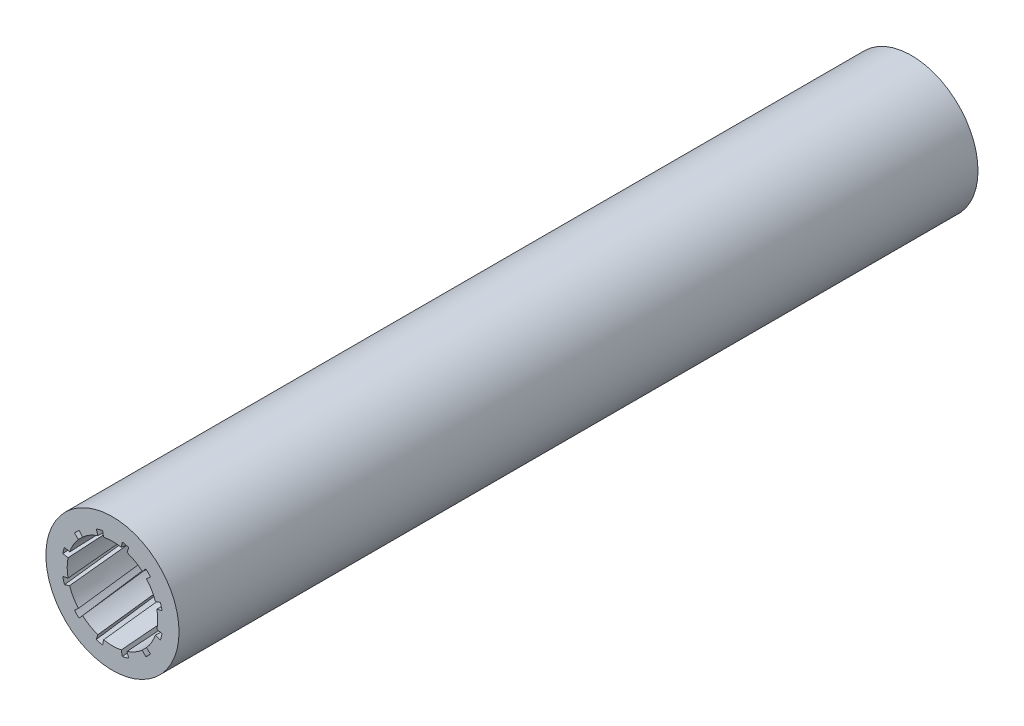
SolidWorks part; units mm, degrees
ref_plane "前视基准面" through (0, 0, 0) normal (0, 0, 1) x (1, 0, 0)
ref_plane "上视基准面" through (0, 0, 0) normal (0, 1, 0) x (1, 0, 0)
ref_plane "右视基准面" through (0, 0, 0) normal (1, 0, 0) x (0, 0, -1)
other "Configuration Table"
sketch "草图1" plane through (0, 0, 0) normal (0, 0, 1) x (1, 0, 0)
  circle A0 centre (0, 0) radius 12.5
  circle A1 centre (0, 0) radius 9.5
  point P5 (0.5665, 0)
  dimension "D1" = 25
  dimension "D2" = 3
extrude "凸台-拉伸1" add sketch "草图1" against normal blind 150 contours A0
sketch "草图2" plane through (0, 0, 0) normal (0, 0, 1) x (1, 0, 0)
  line L0 (0, 0) -> (0, 9.5) construction
  line L1 (-1.8534, 9.3175) -> (-1.6583, 8.3367)
  line L2 (1.8534, 9.3175) -> (1.6583, 8.3367)
  line L3 (1.6583, 8.3367) -> (0, 0) construction
  line L4 (-1.6583, 8.3367) -> (0, 0) construction
  arc A0 (1.6583, 8.3367) -> (-1.6583, 8.3367) centre (0, 0) ccw
  circle A1 centre (0, 0) radius 9.5 construction
  arc A2 (-1.6583, 8.3367) -> (1.6583, 8.3367) centre (0, 0) ccw construction
  arc A3 (1.8534, 9.3175) -> (-1.8534, 9.3175) centre (0, 0) ccw
  dimension "D1" = 1
  dimension "D2" = 11.25
sketch "草图4" plane through (0, 0, 0) normal (0, 0, 1) x (1, 0, 0)
  circle A0 centre (0, 0) radius 9.5 construction
  circle A1 centre (0, 0) radius 9.5
curve "螺旋线/涡状线1" pitch 600 height 150 turns 0.25
sweep "扫描1" add profiles "草图2" path "螺旋线/涡状线1"
pattern_circular "阵列(圆周)1" count 12 over 360 about axis through (0, 0, -150) along (0, 0, 1) of "扫描1"
